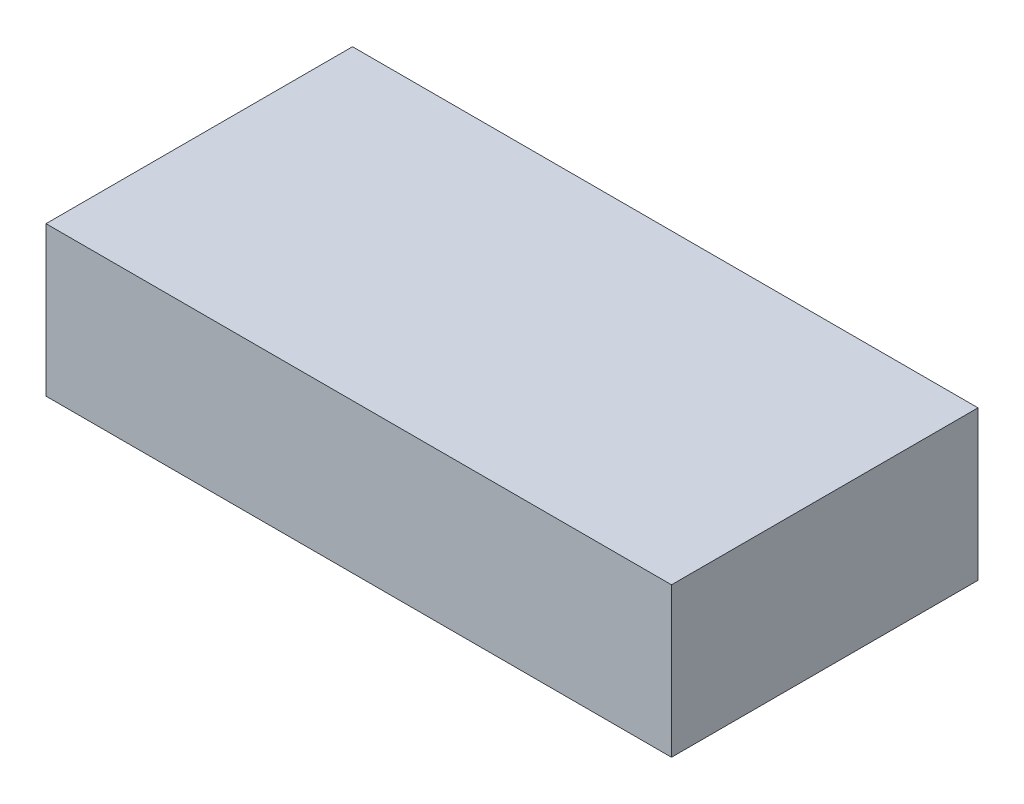
SolidWorks part; units mm, degrees
ref_plane "Front Plane" through (0, 0, 0) normal (0, 0, 1) x (1, 0, 0)
ref_plane "Top Plane" through (0, 0, 0) normal (0, 1, 0) x (1, 0, 0)
ref_plane "Right Plane" through (0, 0, 0) normal (1, 0, 0) x (0, 0, -1)
sketch "Sketch1" plane through (0, 0, 0) normal (0, 1, 0) x (1, 0, 0)
  line L1 (-38.1, -25.4) -> (38.1, -25.4)
  line L2 (-38.1, -25.4) -> (-38.1, 25.4)
  line L3 (-38.1, 25.4) -> (38.1, 25.4)
  line L4 (38.1, -25.4) -> (38.1, 25.4)
  line L5 (-38.1, -25.4) -> (38.1, 25.4) construction
  line L6 (-38.1, 25.4) -> (38.1, -25.4) construction
  point P0 (0, 0)
  dimension "D1" = 76.2
  dimension "D2" = 50.8
extrude "Boss-Extrude1" add sketch "Sketch1" along normal blind 1.6 contours L2 L3 L4 L1
sketch "Sketch2" plane through (0, 1.6, 0) normal (0, 1, 0) x (1, 0, 0)
  line L0 (-36.57, -17.92) -> (-36.57, 17.92)
  line L1 (-36.57, -17.92) -> (36.57, -17.92)
  line L2 (-36.57, 17.92) -> (36.57, 17.92)
  line L3 (36.57, -17.92) -> (36.57, 17.92)
  line L4 (-36.57, -17.92) -> (36.57, 17.92) construction
  line L5 (-36.57, 17.92) -> (36.57, -17.92) construction
  point P1 (0, 0)
  dimension "D1" = 73.14
  dimension "D2" = 35.84
extrude "Boss-Extrude2" add sketch "Sketch2" along normal blind 17.47
sketch "Sketch3" plane through (0, 0, 0) normal (0, -1, 0) x (1, 0, 0)
  line L4 (38.1, 25.4) -> (-38.1, 25.4)
  line L5 (-38.1, 25.4) -> (-38.1, -25.4)
  line L6 (-38.1, -25.4) -> (38.1, -25.4)
  line L7 (38.1, -25.4) -> (38.1, 25.4)
  line L8 (38.1, 25.4) -> (-38.1, 25.4)
  line L9 (-38.1, 25.4) -> (-38.1, -25.4)
  line L10 (-38.1, -25.4) -> (38.1, -25.4)
  line L11 (38.1, -25.4) -> (38.1, 25.4)
  dimension "D1" = 0
extrude "Heat Sink Shave Mod" cut sketch "Sketch3" against normal up to vertex (1.6 mm away)
